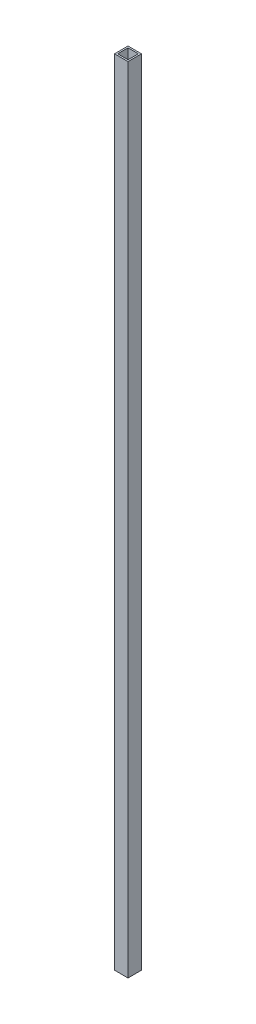
SolidWorks part; units mm, degrees
ref_plane "Front Plane" through (0, 0, 0) normal (0, 0, 1) x (1, 0, 0)
ref_plane "Top Plane" through (0, 0, 0) normal (0, 1, 0) x (1, 0, 0)
ref_plane "Right Plane" through (0, 0, 0) normal (1, 0, 0) x (0, 0, -1)
sketch "Sketch1" plane through (0, 0, 0) normal (0, 1, 0) x (1, 0, 0)
  line L1 (15.8767, 21.8352) -> (24.3767, 21.8352)
  line L2 (15.8767, 21.8352) -> (15.8767, 30.3352)
  line L3 (15.8767, 30.3352) -> (24.3767, 30.3352)
  line L4 (24.3767, 21.8352) -> (24.3767, 30.3352)
  line L5 (16.8767, 29.3352) -> (23.3767, 29.3352)
  line L6 (16.8767, 29.3352) -> (16.8767, 22.8352)
  line L7 (16.8767, 22.8352) -> (23.3767, 22.8352)
  line L8 (23.3767, 29.3352) -> (23.3767, 22.8352)
  dimension "D1" = 8.5
  dimension "D2" = 8.5
  dimension "D3" = 6.5
  dimension "D4" = 6.5
  dimension "D5" = 1
  dimension "D6" = 1
extrude "Boss-Extrude1" add sketch "Sketch1" along normal blind 500
